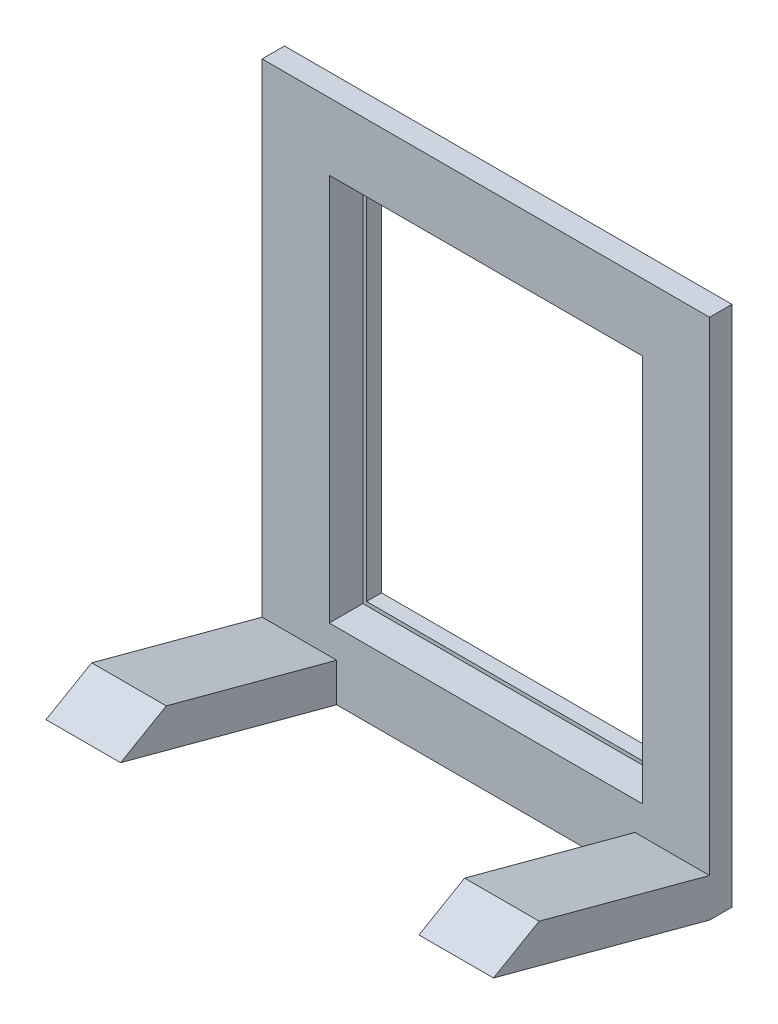
SolidWorks part; units mm, degrees
material "ABS"
ref_plane "Спереди" through (0, 0, 0) normal (0, 0, 1) x (1, 0, 0)
ref_plane "Сверху" through (0, 0, 0) normal (0, 1, 0) x (1, 0, 0)
ref_plane "Справа" through (0, 0, 0) normal (1, 0, 0) x (0, 0, -1)
other "Центр тяжести"
sketch "Эскиз1" plane through (0, 0, 0) normal (0, 0, 1) x (1, 0, 0)
  line L5 (-30, -35) -> (30, -35)
  line L6 (-30, -35) -> (-30, 35)
  line L7 (-30, 35) -> (30, 35)
  line L8 (30, -35) -> (30, 35)
  line L9 (-30, -35) -> (30, 35) construction
  line L10 (-30, 35) -> (30, -35) construction
  line L11 (-20.5, -25.5) -> (20.5, -25.5)
  line L12 (-20.5, -25.5) -> (-20.5, 25.5)
  line L13 (-20.5, 25.5) -> (20.5, 25.5)
  line L14 (20.5, -25.5) -> (20.5, 25.5)
  line L15 (-20.5, -25.5) -> (20.5, 25.5) construction
  line L16 (-20.5, 25.5) -> (20.5, -25.5) construction
  point P0 (0, 0)
  point P5 (0, 0)
  dimension "D1" = 41
  dimension "D2" = 51
  dimension "D3" = 70
  dimension "D4" = 60
extrude "Бобышка-Вытянуть1" add sketch "Эскиз1" along normal blind 4.5 and the other way blind 2
sketch "Эскиз2" plane through (0, 0, 0) normal (0, 0, -1) x (-1, 0, 0)
  line L1 (-21, 26) -> (21, 26)
  line L2 (-21, 26) -> (-21, -26)
  line L3 (-21, -26) -> (21, -26)
  line L4 (21, 26) -> (21, -26)
  line L5 (-21, 26) -> (21, -26) construction
  line L6 (-21, -26) -> (21, 26) construction
  point P0 (0, 0)
  dimension "D1" = 52
  dimension "D2" = 42
extrude "Вырез-Вытянуть2" cut sketch "Эскиз2" against normal through all
sketch "Эскиз3" plane through (0, -35, 0) normal (0, -1, 0) x (-1, 0, 0)
  line L0 (-30, 2) -> (-30, -1.5)
  line L5 (-30, 2) -> (-30, -4.5) construction
  line L6 (-30, -1.5) -> (-28.5, -1.5)
  line L7 (-28.5, -1.5) -> (-28.5, -2.5)
  line L9 (-28.5, -2.5) -> (-27, -2.5)
  line L10 (-27, -2.5) -> (-27, -2)
  line L11 (30, 2) -> (-30, 2) construction
  line L12 (-22.5, 1.5) -> (-22, 1.5)
  line L15 (-22, 1.5) -> (-22, 2)
  line L16 (-22, 2) -> (-30, 2)
  arc A0 (-27, -2) -> (-22.5, 1.5) centre (-22.228, -3.4926) cw
  dimension "D3" = 5
  dimension "D1" = 1.5
  dimension "D2" = 1
  dimension "D4" = 0.5
  dimension "D6" = 8
  dimension "D7" = 3.5
  dimension "D9" = 0.5
  dimension "D10" = 0.5
  dimension "D11" = 1.5
sketch "Эскиз4" plane through (0, 0, -2) normal (0, 0, -1) x (-1, 0, 0)
  line L4 (-30, 35) -> (-30, -35)
  line L6 (-30, 35) -> (-30, -35)
  line L12 (-30, -35) -> (30, -35)
  line L14 (-30, -35) -> (30, -35)
  line L16 (30, -35) -> (30, 35)
  line L17 (30, -35) -> (30, 35)
  line L18 (30, 35) -> (-30, 35)
  line L19 (30, 35) -> (-30, 35)
  dimension "D1" = 0
sweep "Вырез-По траектории1" cut profiles "Эскиз3" path "Эскиз4"
sketch "Эскиз5" plane through (30, 0, 0) normal (1, 0, 0) x (0, 0, -1)
  line L0 (-4.5, -35) -> (-21.8653, -35) construction
  line L1 (-4.5, -35) -> (-33.4778, -27.2354)
  line L2 (-33.4778, -27.2354) -> (-27.3541, -23.6999)
  line L3 (-27.3541, -23.6999) -> (-4.5, -29.8236)
  line L4 (-4.5, -35) -> (-4.5, 35) construction
  line L5 (-4.5, -29.8236) -> (-4.5, -35)
  line L9 (-4.5, -35) -> (-1.5, -35)
  line L10 (-1.5, -35) -> (-1.5, 35)
  line L11 (-1.5, 35) -> (-4.5, 35)
  line L12 (-4.5, 35) -> (-4.5, -35)
  line L13 (-4.5, -35) -> (-1.5, -35)
  line L15 (-1.5, 35) -> (-4.5, 35)
  line L17 (-1.5, -35) -> (-1.5, 35)
  line M12 (-4.5, 35) -> (-4.5, -35)
  dimension "D1" = 15
  dimension "D2" = 5
  dimension "D3" = 45
  dimension "D4" = 30
  dimension "D5" = 0
extrude "Бобышка-Вытянуть2" add sketch "Эскиз5" against normal blind 10 contours L3 L2 L1 M12
mirror "Зеркальное отражение1" about plane through (0, 0, 0) normal (1, 0, 0) of "Бобышка-Вытянуть2"
sketch "Эскиз6" plane through (30, 0, 0) normal (1, 0, 0) x (0, 0, -1)
  line L0 (-4.5, -35) -> (-1.5, -35.8038)
  line L1 (-1.5, -35.8038) -> (-1.5, -35)
  line L2 (-1.5, -35) -> (-4.5, -35)
  line L3 (-4.5, -35) -> (-33.4778, -27.2354) construction
extrude "Бобышка-Вытянуть3" [suppressed] add sketch "Эскиз6" against normal blind 60
